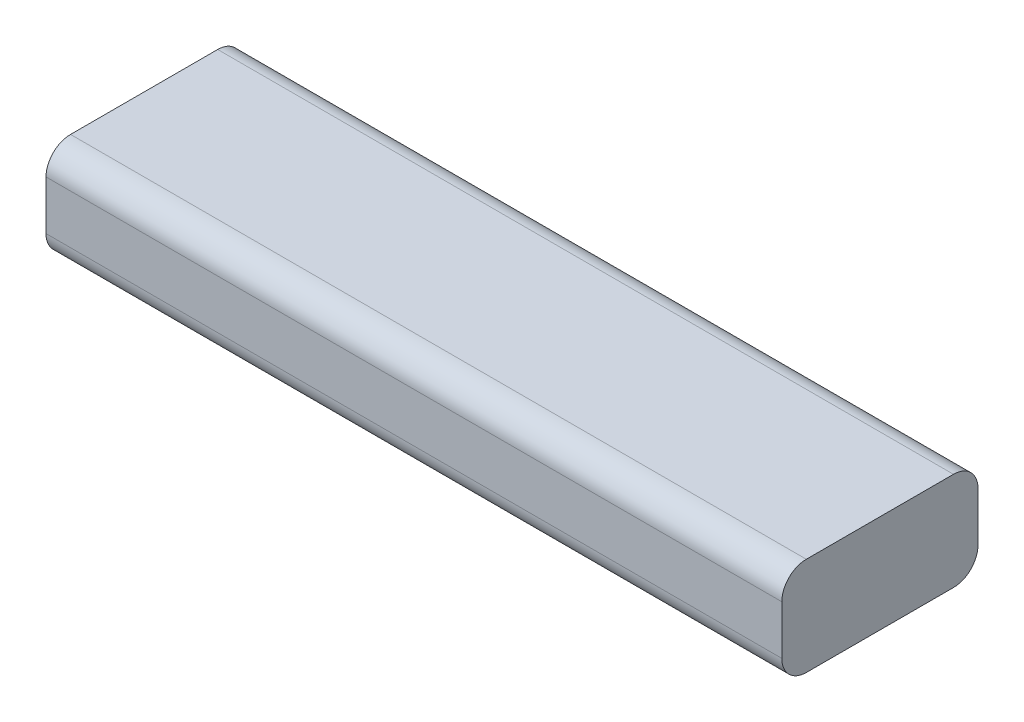
SolidWorks part; units mm, degrees
ref_plane "Front Plane" through (0, 0, 0) normal (0, 0, 1) x (1, 0, 0)
ref_plane "Top Plane" through (0, 0, 0) normal (0, 1, 0) x (1, 0, 0)
ref_plane "Right Plane" through (0, 0, 0) normal (1, 0, 0) x (0, 0, -1)
sketch "Sketch1" plane through (0, 0, 0) normal (0, 1, 0) x (1, 0, 0)
  line L1 (-75, 20) -> (75, 20)
  line L2 (-75, 20) -> (-75, -20)
  line L3 (-75, -20) -> (75, -20)
  line L4 (75, 20) -> (75, -20)
  dimension "D1" = 75
  dimension "D2" = 150
  dimension "D3" = 20
  dimension "D4" = 40
extrude "Boss-Extrude1" add sketch "Sketch1" along normal blind 20
sketch "Sketch2" plane through (0, 0, 0) normal (0, -1, 0) x (1, 0, 0)
  line L0 (75, -20) -> (-75, -20) construction
  line L1 (70, -15) -> (40, -15)
  line L2 (70, -15) -> (70, 15)
  line L3 (70, 15) -> (40, 15)
  line L4 (40, -15) -> (40, 15)
  line L5 (-75, 20) -> (75, 20) construction
  line L6 (75, 20) -> (75, -20) construction
  dimension "D1" = 5
  dimension "D2" = 5
  dimension "D3" = 5
  dimension "D4" = 30
extrude "Cut-Extrude1" cut sketch "Sketch2" against normal blind 5 from offset 1 offset against normal yes
sketch "Sketch7" plane through (-75, 0, 0) normal (-1, 0, 0) x (0, 0, 1)
  line L0 (20, 20) -> (20, 0) construction
  line L1 (-20, 0) -> (20, 0) construction
  circle A0 centre (12, 3.5) radius 2
  dimension "D1" = 4
  dimension "D2" = 8
  dimension "D3" = 3.5
extrude "Cut-Extrude3" cut sketch "Sketch7" against normal blind 140
fillet "Fillet1" radius 5 4 edges at (0, 0, -20) (0, 0, 20) (0, 20, -20) (0, 20, 20)
sketch "Sketch9" plane through (-75, 0, 0) normal (-1, 0, 0) x (0, 0, 1)
  line L0 (-15, 0) -> (15, 0) construction
  line L1 (-20, 15) -> (-20, 5) construction
  circle A0 centre (0, 10) radius 9
  dimension "D1" = 18
  dimension "D2" = 10
  dimension "D3" = 20
extrude "Cut-Extrude5" cut sketch "Sketch9" against normal blind 50 from offset 25 offset against normal yes
sketch "Sketch8" plane through (-75, 0, 0) normal (-1, 0, 0) x (0, 0, 1)
  line L0 (20, 15) -> (20, 5) construction
  line L1 (-15, 0) -> (15, 0) construction
  circle A0 centre (0, 10) radius 2
  dimension "D1" = 4
  dimension "D2" = 20
  dimension "D3" = 10
extrude "Cut-Extrude4" cut sketch "Sketch8" against normal blind 62
